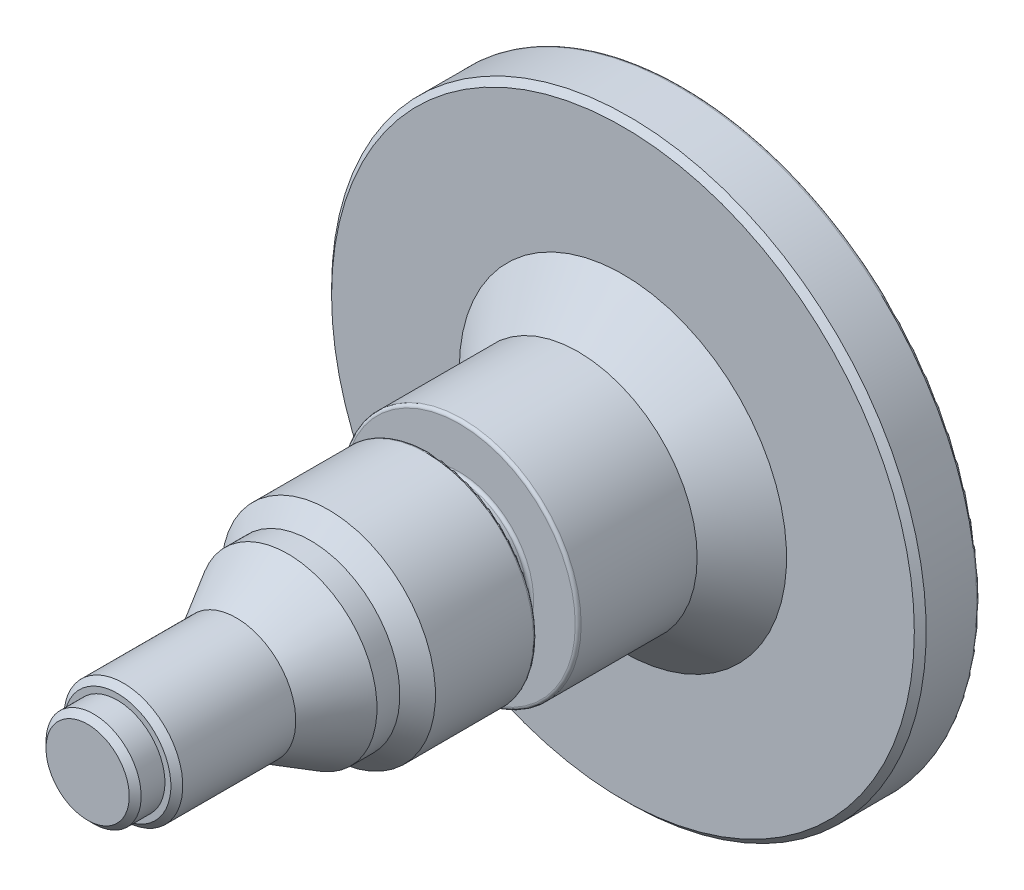
SolidWorks part; units mm, degrees
ref_plane "Front Plane" through (0, 0, 0) normal (0, 0, 1) x (1, 0, 0)
ref_plane "Top Plane" through (0, 0, 0) normal (0, 1, 0) x (1, 0, 0)
ref_plane "Right Plane" through (0, 0, 0) normal (1, 0, 0) x (0, 0, -1)
sketch "Sketch5" plane through (0, 0, 0) normal (0, 1, 0) x (1, 0, 0)
  line L0 (0, 100.0204) -> (50, 100.0204)
  line L1 (50, 100.0204) -> (50, 90.0204)
  line L2 (50, 90.0204) -> (27.5204, 90.0204)
  line L3 (27.5204, 90.0204) -> (20, 82.5)
  line L4 (20, 82.5) -> (20, 62.5)
  line L7 (15, 33.6603) -> (10, 25)
  line L8 (10, 25) -> (10, 5)
  line L9 (10, 5) -> (8, 5)
  line L10 (8, 5) -> (8, 0)
  line L11 (8, 0) -> (0, 0)
  line L12 (0, 100.0204) -> (0, 0)
  line L13 (15, 37.5) -> (15, 33.6603)
  line L15 (20, 62.5) -> (12, 62.5)
  line L16 (12, 62.5) -> (12, 57.5)
  line L17 (12, 57.5) -> (18, 57.5)
  line L18 (18, 57.5) -> (18, 40.5)
  line L19 (18, 40.5) -> (15, 37.5)
  dimension "D2" = 5
  dimension "D3" = 50
  dimension "D4" = 10
  dimension "D6" = 45
  dimension "D7" = 20
  dimension "D8" = 30
  dimension "D9" = 10
  dimension "D10" = 20
  dimension "D11" = 45
  dimension "D13" = 5
  dimension "D15" = 20
  dimension "D16" = 8
  dimension "D17" = 18
  dimension "D18" = 15
  dimension "D19" = 20
  dimension "D22" = 8
ref_axis "Axis1" through (0, 0, -100.0204) along (0, 0, 1)
revolve "Revolve1" add sketch "Sketch5" angle 360 about axis through (0, 0, -100.0204) along (0, 0, 1)
chamfer "Chamfer1" distance 1 angle 45 3 edges at (-10, 0, -5) (-8, 0, 0) (-50, 0, -90.0204)
fillet "Fillet1" radius 0.5 5 edges at (-12, 0, -57.5) (-12, 0, -62.5) (-18, 0, -57.5) (-20, 0, -62.5) (-50, 0, -100.0204)
